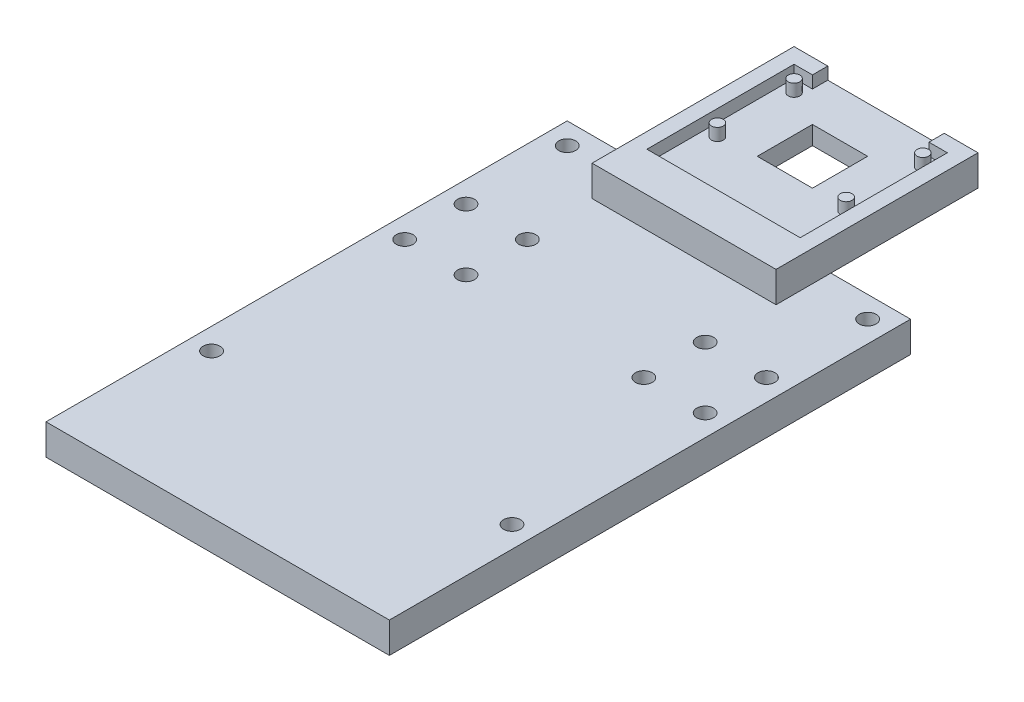
SolidWorks part; units mm, degrees
ref_plane "Front Plane" through (0, 0, 0) normal (0, 0, 1) x (1, 0, 0)
ref_plane "Top Plane" through (0, 0, 0) normal (0, 1, 0) x (1, 0, 0)
ref_plane "Right Plane" through (0, 0, 0) normal (1, 0, 0) x (0, 0, -1)
sketch "Sketch1" plane through (0, 0, 0) normal (0, 1, 0) x (1, 0, 0)
  line L1 (-53.9521, 45.0449) -> (2.0479, 45.0449)
  line L2 (-53.9521, 45.0449) -> (-53.9521, -39.9551)
  line L3 (-53.9521, -39.9551) -> (2.0479, -39.9551)
  line L4 (2.0479, 45.0449) -> (2.0479, -39.9551)
  dimension "D1" = 85
  dimension "D2" = 56
extrude "Boss-Extrude1" add sketch "Sketch1" along normal blind 5
sketch "Sketch2" plane through (0, 0, 0) normal (0, -1, 0) x (-1, 0, 0)
  line L0 (-2.0479, 45.0449) -> (53.9521, 45.0449) construction
  line L2 (53.9521, 45.0449) -> (53.9521, -39.9551) construction
  line L3 (-2.0479, -39.9551) -> (-2.0479, 45.0449) construction
  circle A0 centre (50.4521, 41.5449) radius 1.375
  circle A1 centre (1.4521, 41.5449) radius 1.375
  circle A2 centre (50.4521, -16.4551) radius 1.375
  circle A3 centre (1.4521, -16.4551) radius 1.375
  dimension "D1" = 2.75
  dimension "D2" = 3.5
  dimension "D4" = 2.75
  dimension "D7" = 2.75
  dimension "D10" = 2.75
  dimension "D3" = 3.5
  dimension "D5" = 3.5
  dimension "D6" = 3.5
  dimension "D8" = 3.5
  dimension "D9" = 58
  dimension "D11" = 58
  dimension "D12" = 3.5
extrude "Cut-Extrude1" cut sketch "Sketch2" against normal blind 5
sketch "Sketch3" plane through (0, 0, 0) normal (0, -1, 0) x (-1, 0, 0)
  line L0 (-2.0479, 45.0449) -> (53.9521, 45.0449) construction
  line L1 (53.9521, 45.0449) -> (53.9521, -39.9551) construction
  line L2 (-2.0479, -39.9551) -> (-2.0479, 45.0449) construction
  circle A0 centre (50.4521, 25.0449) radius 1.375
  circle A1 centre (50.4521, 15.0449) radius 1.375
  circle A2 centre (40.4521, 15.0449) radius 1.375
  circle A3 centre (40.4521, 25.0449) radius 1.375
  circle A4 centre (1.4521, 25.0449) radius 1.375
  circle A5 centre (11.4521, 25.0449) radius 1.375
  circle A6 centre (1.4521, 15.0449) radius 1.375
  circle A7 centre (11.4521, 15.0449) radius 1.375
  dimension "D1" = 2.75
  dimension "D3" = 3.5
  dimension "D4" = 2.75
  dimension "D5" = 3.5
  dimension "D6" = 10
  dimension "D7" = 2.75
  dimension "D8" = 2.75
  dimension "D9" = 10
  dimension "D10" = 10
  dimension "D11" = 2.75
  dimension "D13" = 3.5
  dimension "D14" = 2.75
  dimension "D15" = 10
  dimension "D16" = 2.75
  dimension "D17" = 10
  dimension "D18" = 2.75
  dimension "D19" = 10
  dimension "D20" = 3.5
  dimension "D2" = 20
  dimension "D12" = 20
extrude "Cut-Extrude2" cut sketch "Sketch3" against normal blind 5
sketch "Sketch5" plane through (0, 5, 0) normal (0, 1, 0) x (1, 0, 0)
  line L0 (2.0479, 45.0449) -> (-53.9521, 45.0449) construction
  line L1 (-10.9521, 45.0449) -> (-40.9521, 45.0449)
  line L2 (-10.9521, 45.0449) -> (-10.9521, 36.1065)
  line L3 (-10.9521, 36.1065) -> (-40.9521, 36.1065)
  line L4 (-40.9521, 45.0449) -> (-40.9521, 36.1065)
  line L5 (2.0479, -39.9551) -> (2.0479, 45.0449) construction
  line L6 (-53.9521, 45.0449) -> (-53.9521, -39.9551) construction
  dimension "D1" = 30
  dimension "D2" = 13
  dimension "D3" = 13
extrude "Boss-Extrude2" add sketch "Sketch5" along normal blind 5
sketch "Sketch6" plane through (0, 0, -45.0449) normal (0, 0, -1) x (-1, 0, 0)
  line L0 (40.9521, 10) -> (40.9521, 5) construction
  line L1 (10.9521, 10) -> (40.9521, 10)
  line L2 (10.9521, 10) -> (10.9521, 5)
  line L3 (10.9521, 5) -> (40.9521, 5)
  line L4 (40.9521, 10) -> (40.9521, 5)
  dimension "D1" = 5
extrude "Boss-Extrude3" add sketch "Sketch6" along normal blind 24
sketch "Sketch8" plane through (0, 10, 0) normal (0, 1, 0) x (1, 0, 0)
  line L0 (-40.9521, 69.0449) -> (-40.9521, 36.1065) construction
  line L1 (-38.4521, 66.5449) -> (-35.4521, 66.5449)
  line L2 (-38.4521, 66.5449) -> (-38.4521, 42.5449)
  line L3 (-38.4521, 42.5449) -> (-13.4521, 42.5449)
  line L4 (-13.4521, 66.5449) -> (-13.4521, 42.5449)
  line L5 (-10.9521, 36.1065) -> (-10.9521, 69.0449) construction
  line L6 (-40.9521, 69.0449) -> (-10.9521, 69.0449) construction
  line L7 (-16.4521, 66.5449) -> (-13.4521, 66.5449)
  line L9 (-35.4521, 66.5449) -> (-35.4521, 69.0449)
  line L10 (-35.4521, 69.0449) -> (-16.4521, 69.0449)
  line L11 (-16.4521, 66.5449) -> (-16.4521, 69.0449)
  dimension "D1" = 25
  dimension "D2" = 24
  dimension "D3" = 2.5
  dimension "D4" = 2.5
  dimension "D5" = 2.5
  dimension "D6" = 3
  dimension "D7" = 3
extrude "Cut-Extrude3" cut sketch "Sketch8" against normal blind 2
sketch "Sketch9" plane through (0, 8, 0) normal (0, 1, 0) x (1, 0, 0)
  line L0 (-38.4521, 66.5449) -> (-38.4521, 42.5449) construction
  line L1 (-30.4521, 61.5449) -> (-21.4521, 61.5449)
  line L2 (-30.4521, 61.5449) -> (-30.4521, 52.5449)
  line L3 (-30.4521, 52.5449) -> (-21.4521, 52.5449)
  line L4 (-21.4521, 61.5449) -> (-21.4521, 52.5449)
  line L5 (-13.4521, 42.5449) -> (-13.4521, 66.5449) construction
  line L6 (-35.4521, 66.5449) -> (-38.4521, 66.5449) construction
  dimension "D1" = 9
  dimension "D2" = 8
  dimension "D3" = 8
  dimension "D4" = 5
  dimension "D5" = 9
extrude "Cut-Extrude4" cut sketch "Sketch9" against normal up to surface (3 mm away) up to face at (-22.2021, 5, -63.0449)
sketch "Sketch10" plane through (0, 8, 0) normal (0, 1, 0) x (1, 0, 0)
  line L0 (-35.4521, 66.5449) -> (-38.4521, 66.5449) construction
  line L1 (-38.4521, 66.5449) -> (-38.4521, 42.5449) construction
  line L2 (-13.4521, 66.5449) -> (-16.4521, 66.5449) construction
  line L3 (-13.4521, 42.5449) -> (-13.4521, 66.5449) construction
  line L4 (-38.4521, 66.5449) -> (-38.4521, 42.5449) construction
  circle A0 centre (-36.4521, 64.5449) radius 0.95
  circle A1 centre (-15.4521, 64.5449) radius 0.95
  circle A2 centre (-15.4521, 52.0449) radius 0.95
  circle A3 centre (-36.4521, 52.0449) radius 0.95
  dimension "D1" = 1.9
  dimension "D2" = 2
  dimension "D3" = 2
  dimension "D4" = 1.9
  dimension "D5" = 2
  dimension "D6" = 2
  dimension "D7" = 1.9
  dimension "D8" = 2
  dimension "D9" = 12.5
  dimension "D10" = 1.9
  dimension "D11" = 2
  dimension "D12" = 12.5
extrude "Boss-Extrude4" add sketch "Sketch10" along normal blind 2
